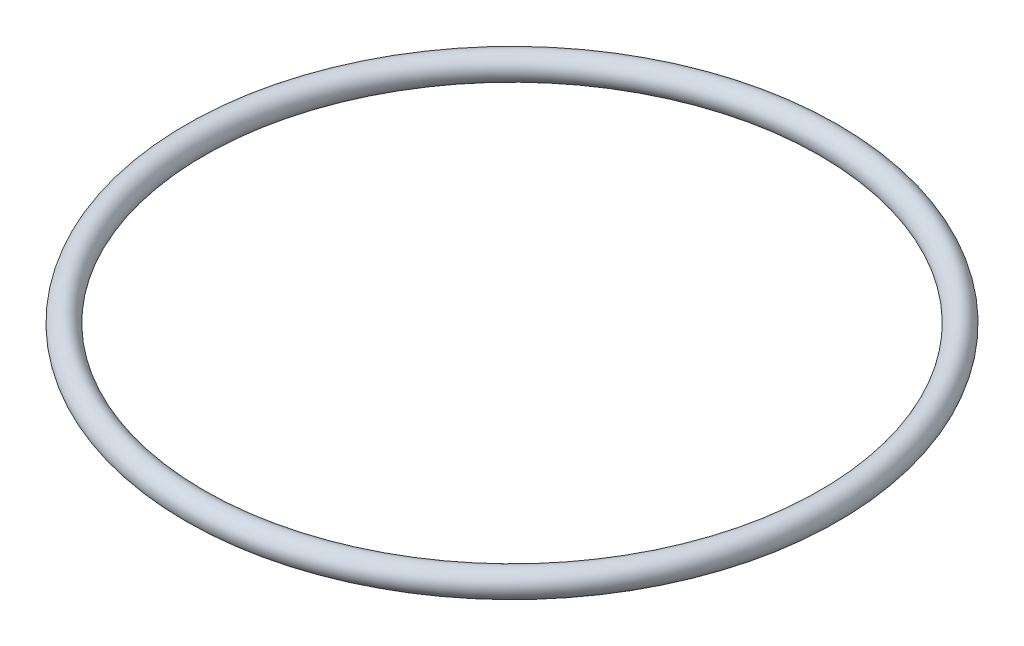
SolidWorks part; units mm, degrees
ref_plane "Front Plane" through (0, 0, 0) normal (0, 0, 1) x (1, 0, 0)
ref_plane "Top Plane" through (0, 0, 0) normal (0, 1, 0) x (1, 0, 0)
ref_plane "Right Plane" through (0, 0, 0) normal (1, 0, 0) x (0, 0, -1)
sketch "Sketch2" plane through (0, 0, 0) normal (0, 0, 1) x (1, 0, 0)
  line L0 (0, 0) -> (-19.8438, 0) construction
  line L1 (0, -25.6365) -> (0, 25.6365) construction
  circle A0 centre (-19.8438, 0) radius 0.7937
  point P7 (0, 0)
  dimension "D1" = 1.5875
  dimension "D2" = 19.8438
revolve "Revolve1" add sketch "Sketch2" angle 360 about L1
